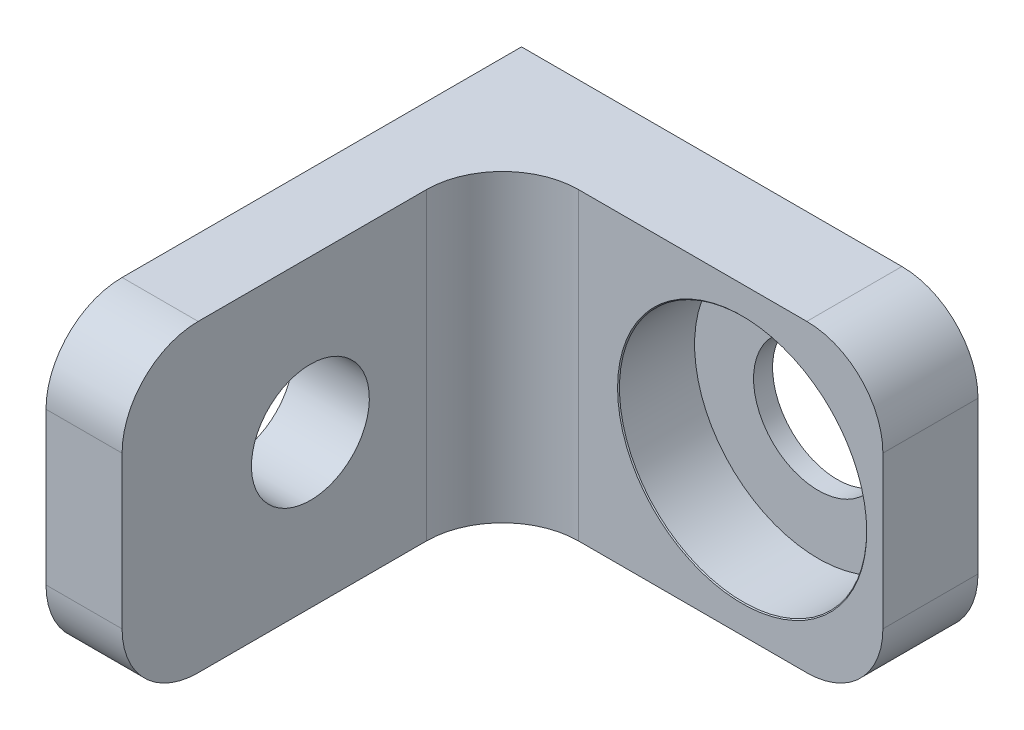
SolidWorks part; units mm, degrees
ref_plane "Plano frontal" through (0, 0, 0) normal (0, 0, 1) x (1, 0, 0)
ref_plane "Plano superior" through (0, 0, 0) normal (0, 1, 0) x (1, 0, 0)
ref_plane "Plano direito" through (0, 0, 0) normal (1, 0, 0) x (0, 0, -1)
sketch "Esboço1" plane through (0, 0, 0) normal (0, 0, 1) x (1, 0, 0)
  line L1 (-12, 6) -> (0, 6)
  line L2 (-12, 6) -> (-12, -2)
  line L3 (-12, -2) -> (0, -2)
  line L4 (0, 6) -> (0, -2)
  dimension "D1" = 8
  dimension "D2" = 12
extrude "Ressalto-extrusão1" add sketch "Esboço1" along normal blind 2.5
sketch "Esboço2" plane through (0, 0, 2.5) normal (0, 0, 1) x (1, 0, 0)
  line L0 (-12, 2) -> (0, 2) construction
  line L1 (-12, 6) -> (-12, -2) construction
  line L2 (0, -2) -> (0, 6) construction
  circle A0 centre (-3.7, 2) radius 1.7
  point P9 (-5.4, 2)
  dimension "D2" = 3.4
  dimension "D1" = 6.6
sketch "Esboço3" plane through (0, 0, 2.5) normal (0, 0, 1) x (1, 0, 0)
  line L0 (-12, -2) -> (0, -2) construction
  line L1 (-12, 6) -> (-10, 6)
  line L2 (-12, 6) -> (-12, -2)
  line L3 (-12, -2) -> (-10, -2)
  line L4 (-10, 6) -> (-10, -2)
  dimension "D1" = 2
extrude "Ressalto-extrusão2" add sketch "Esboço3" along normal blind 10
sketch "Esboço6" plane through (-10, 0, 0) normal (1, 0, 0) x (0, 0, -1)
  line L0 (-12.5, 2) -> (-2.5011, 2) construction
  line L1 (-12.5, -2) -> (-12.5, 6) construction
  line L2 (-2.5, -2) -> (-2.5, 6) construction
  circle A0 centre (-7.55, 2) radius 1.55
  point P6 (-6, 2)
  point P9 (0, 0)
  dimension "D2" = 3.1
  dimension "D1" = 3.5
hole_wizard "Rebaixo para parafuso com cabeça redonda de M33" positions "Esboço9" profile "Esboço10" counterbore size "M3" standard "ISO" end condition through all
sketch "Esboço9" plane through (0, 0, 2.5) normal (0, 0, 1) x (1, 0, 0)
  point P0 (-3.7, 2)
sketch "Esboço10" plane through (-3.7, 2, 2.5) normal (1, 0, 0) x (0, -1, 0)
  line L0 (0, 0) -> (0, 2.5)
  line L1 (0, 2.5) -> (1.7, 2.5)
  line L3 (1.7, 2.5) -> (1.7, 2)
  line L4 (3.25, 2) -> (1.7, 2)
  line L5 (3.25, 2) -> (3.25, 0.025)
  line L6 (3.25, 0.025) -> (3.275, 0)
  line L7 (3.275, 0) -> (0, 0)
  line L8 (-3.25, 0.025) -> (-3.275, 0) construction
  line L11 (0, -6.35) -> (0, 107.95) construction
  dimension "Thru Hole Dia." = 3.4
  dimension "Thru Hole Depth" = 2.5
  dimension "C'Bore Dia." = 6.5
  dimension "C'Bore Depth" = 2
  dimension "Near C'Sink Dia." = 6.55
  dimension "Near C'Sink Angle" = 90
fillet "Filete1" radius 2 1 edges at (-10, 2, 2.5)
fillet "Filete2" radius 2 4 edges at (0, 6, 1.25) (0, -2, 1.25) (-11, -2, 12.5) (-11, 6, 12.5)
extrude "Corte-extrusão2" cut sketch "Esboço6" against normal up to next
